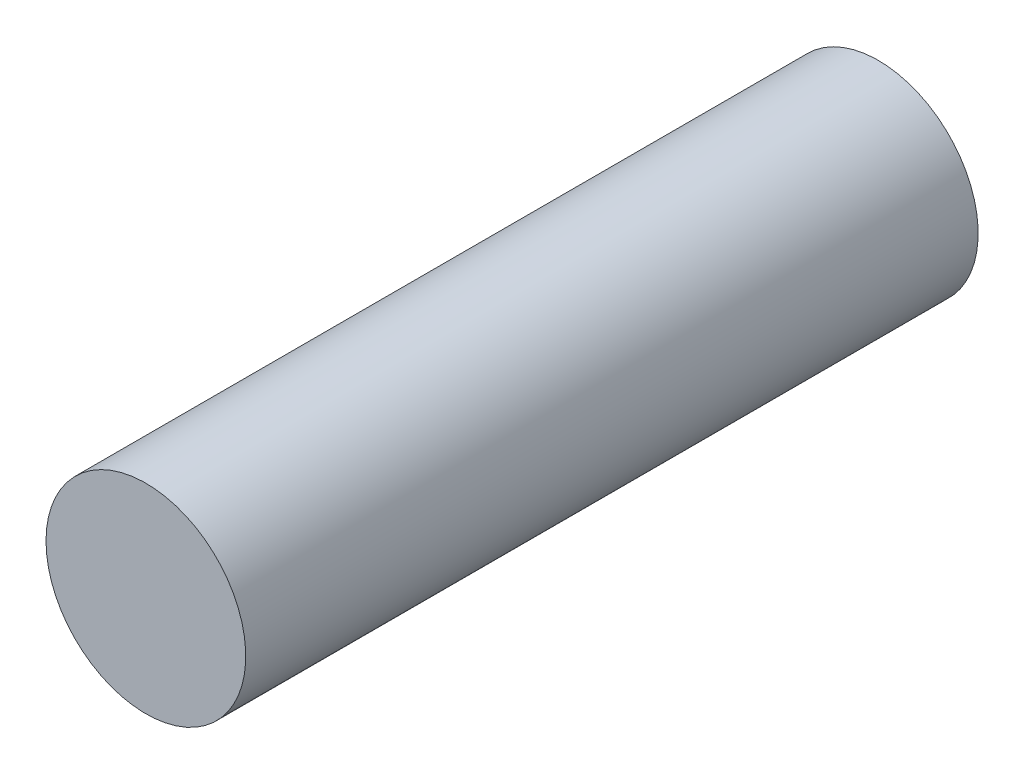
SolidWorks part; units mm, degrees
ref_plane "Front Plane" through (0, 0, 0) normal (0, 0, 1) x (1, 0, 0)
ref_plane "Top Plane" through (0, 0, 0) normal (0, 1, 0) x (1, 0, 0)
ref_plane "Right Plane" through (0, 0, 0) normal (1, 0, 0) x (0, 0, -1)
sketch "Sketch1" plane through (0, 0, 0) normal (0, 1, 0) x (1, 0, 0)
  line L0 (0, 0) -> (0, -11)
  line L1 (0, -11) -> (-1.5, -11)
  line L2 (-1.5, -11) -> (-1.5, 0)
  line L3 (-1.5, 0) -> (0, 0)
  dimension "D1" = 1.5
  dimension "D2" = 11
revolve "Revolve1" add sketch "Sketch1" angle 360 about L0
